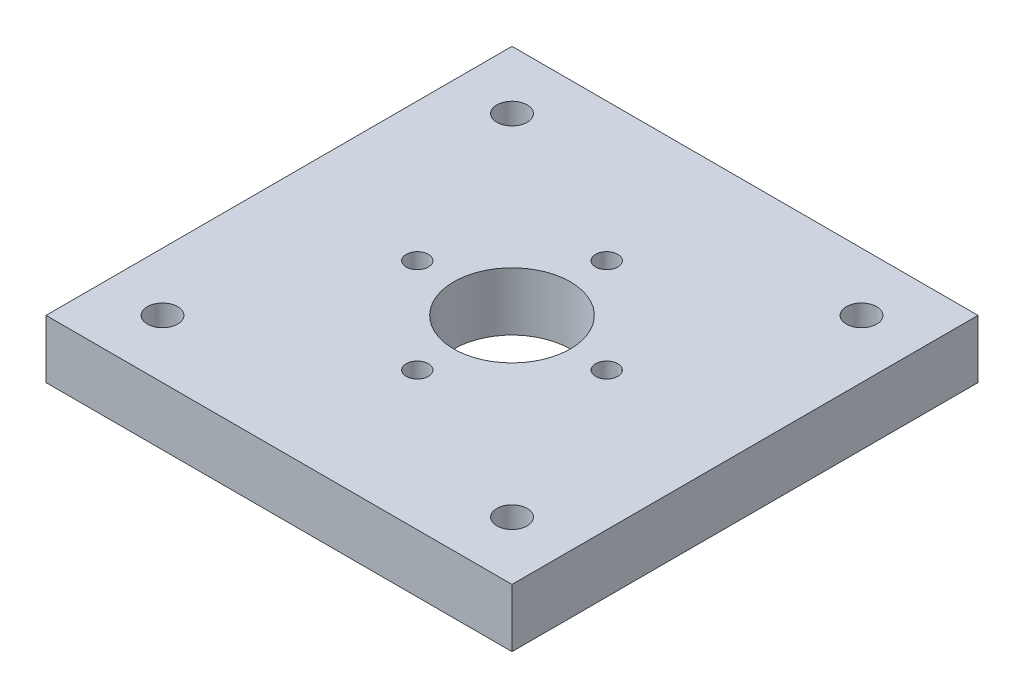
SolidWorks part; units mm, degrees
ref_plane "Front Plane" through (0, 0, 0) normal (0, 0, 1) x (1, 0, 0)
ref_plane "Top Plane" through (0, 0, 0) normal (0, 1, 0) x (1, 0, 0)
ref_plane "Right Plane" through (0, 0, 0) normal (1, 0, 0) x (0, 0, -1)
sketch "Sketch1" plane through (0, 0, 0) normal (0, 1, 0) x (1, 0, 0)
  line L1 (-2, 2) -> (2, 2)
  line L2 (-2, 2) -> (-2, -2)
  line L3 (-2, -2) -> (2, -2)
  line L4 (2, 2) -> (2, -2)
  line L5 (-2, 2) -> (2, -2) construction
  line L6 (-2, -2) -> (2, 2) construction
  point P0 (0, 0)
  dimension "D1" = 4
  dimension "D2" = 4
extrude "Boss-Extrude1" add sketch "Sketch1" along normal blind 0.5
sketch "Sketch2" plane through (0, 0.5, 0) normal (0, 1, 0) x (1, 0, 0)
  line L0 (0, 0) -> (0.851, 0) construction
  circle A0 centre (-1.5, -1.5) radius 0.13
  circle A1 centre (1.5, -1.5) radius 0.13
  circle A2 centre (1.5, 1.5) radius 0.13
  circle A3 centre (-1.5, 1.5) radius 0.13
  dimension "D1" = 0.26
  dimension "D2" = 3
  dimension "D3" = 1.5
  dimension "D4" = 1.5
extrude "Cut-Extrude1" cut sketch "Sketch2" against normal blind 0.5
sketch "Sketch3" plane through (0, 0, 0) normal (0, -1, 0) x (1, 0, 0)
  circle A0 centre (0, 0) radius 0.5
  dimension "D1" = 1
extrude "Cut-Extrude2" cut sketch "Sketch3" against normal blind 0.5 contours A0
sketch "Sketch4" plane through (0, 0, 0) normal (0, -1, 0) x (1, 0, 0)
  circle A0 centre (0, 0) radius 0.813
  circle A1 centre (0, 0.813) radius 0.095
  dimension "D1" = 1.626
  dimension "D2" = 0.19
extrude "Cut-Extrude3" cut sketch "Sketch4" against normal through all contours A1
pattern_circular "CirPattern1" count 4 over 360 about axis through (0, 0, 0) along (0, 1, 0) of "Cut-Extrude3"
